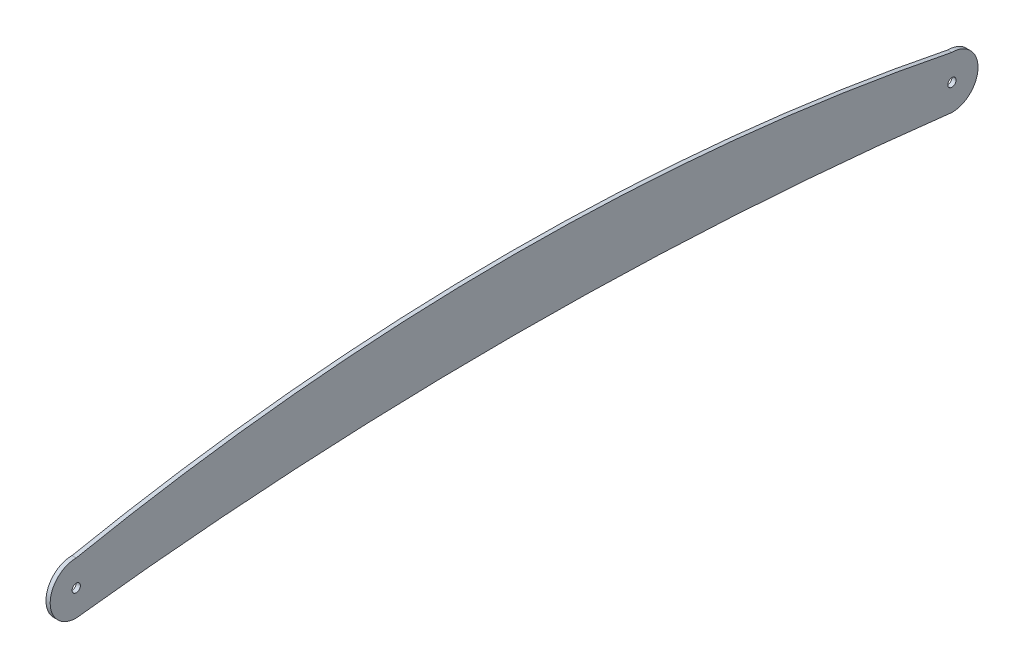
SolidWorks part; units mm, degrees
material "AISI 1010 Steel, hot rolled bar"
ref_plane "Front Plane" through (0, 0, 0) normal (0, 0, 1) x (1, 0, 0)
ref_plane "Top Plane" through (0, 0, 0) normal (0, 1, 0) x (1, 0, 0)
ref_plane "Right Plane" through (0, 0, 0) normal (1, 0, 0) x (0, 0, -1)
sketch "Sketch1" plane through (0, 0, 0) normal (1, 0, 0) x (0, 0, -1)
  line L0 (270.0845, 0) -> (254.2095, 0) construction
  line L1 (-260.7755, 0) -> (-263.3155, 0) construction
  line L2 (6.769, 0) -> (0, 0) construction
  circle A0 centre (-263.3155, 0) radius 2.54
  circle A1 centre (270.0845, 0) radius 2.54
  circle A2 centre (-263.3155, 0) radius 15.875
  circle A3 centre (270.0845, 0) radius 15.875
  arc A4 (-263.3155, -15.875) -> (270.0845, -15.875) centre (3.3845, -2247.8567) cw
  arc A5 (-263.3155, 15.875) -> (270.0845, 15.875) centre (3.3845, -1302.6969) cw
  point P18 (270.0845, 0)
  dimension "D2" = 5.08
  dimension "D3" = 31.75
  dimension "D1" = 533.4
extrude "Boss-Extrude1" add sketch "Sketch1" along normal blind 2.54 contours A5 A2 A4 A3 | A2 A4 A0 | A3 A4 A1
sketch "Sketch2" plane through (0, 0, 0) normal (1, 0, 0) x (0, 0, -1)
  line L0 (270.0845, 0) -> (321.5456, 0.3944)
  line L1 (270.0845, 0) -> (270.0845, 61.0048)
  circle A0 centre (270.0845, 0) radius 2.54
